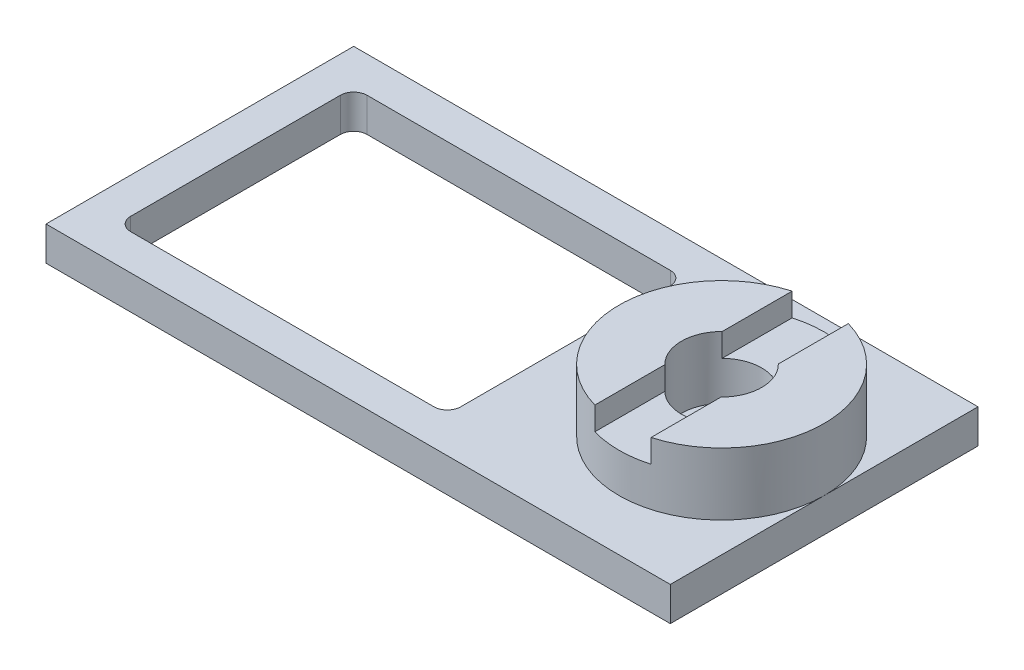
SolidWorks part; units mm, degrees
ref_plane "Alzado" through (0, 0, 0) normal (0, 0, 1) x (1, 0, 0)
ref_plane "Planta" through (0, 0, 0) normal (0, 1, 0) x (1, 0, 0)
ref_plane "Vista lateral" through (0, 0, 0) normal (1, 0, 0) x (0, 0, -1)
sketch "Croquis1" plane through (0, 0, 0) normal (0, 1, 0) x (1, 0, 0)
  line L1 (-350, -172.5) -> (350, -172.5)
  line L2 (-350, -172.5) -> (-350, 172.5)
  line L3 (-350, 172.5) -> (350, 172.5)
  line L4 (350, -172.5) -> (350, 172.5)
  line L5 (-350, -172.5) -> (350, 172.5) construction
  line L6 (-350, 172.5) -> (350, -172.5) construction
  point P0 (0, 0)
  dimension "D1" = 345
  dimension "D2" = 700
extrude "Saliente-Extruir1" add sketch "Croquis1" along normal blind 38.1
sketch "Croquis2" plane through (0, 38.1, 0) normal (0, 1, 0) x (1, 0, 0)
  line L0 (-350, 0) -> (350, 0) construction
  line L1 (-350, 172.5) -> (-350, -172.5) construction
  line L2 (350, -172.5) -> (350, 172.5) construction
  line L3 (350, 172.5) -> (-350, 172.5) construction
  line L4 (60, -132.5) -> (-310, -132.5)
  line L5 (60, -132.5) -> (60, 132.5)
  line L6 (60, 132.5) -> (-310, 132.5)
  line L7 (-310, -132.5) -> (-310, 132.5)
  line L8 (60, -132.5) -> (-310, 132.5) construction
  line L9 (60, 132.5) -> (-310, -132.5) construction
  point P6 (-125, 0)
  dimension "D1" = 40
  dimension "D2" = 40
  dimension "D3" = 370
extrude "Cortar-Extruir1" cut sketch "Croquis2" against normal blind 38.1
fillet "Redondeo1" radius 15 4 edges at (-310, 19.05, -132.5) (-310, 19.05, 132.5) (60, 19.05, 132.5) (60, 19.05, -132.5)
sketch "Croquis3" plane through (0, 38.1, 0) normal (0, 1, 0) x (1, 0, 0)
  line L0 (235, 172.5) -> (235, -172.5) construction
  line L1 (350, 172.5) -> (-350, 172.5) construction
  line L2 (-350, -172.5) -> (350, -172.5) construction
  line L3 (350, -172.5) -> (350, 172.5) construction
  circle A0 centre (235, 0) radius 115
  dimension "D2" = 230
  dimension "D1" = 115
extrude "Saliente-Extruir2" add sketch "Croquis3" along normal blind 70
sketch "Croquis4" plane through (0, 108.1, 0) normal (0, 1, 0) x (1, 0, 0)
  circle A0 centre (235, 0) radius 45
  dimension "D1" = 90
extrude "Cortar-Extruir2" cut sketch "Croquis4" against normal blind 70
sketch "Croquis5" plane through (0, 108.1, 0) normal (0, 1, 0) x (1, 0, 0)
  line L1 (203.5, -123.5371) -> (266.5, -123.5371)
  line L2 (203.5, -123.5371) -> (203.5, 123.5371)
  line L3 (203.5, 123.5371) -> (266.5, 123.5371)
  line L4 (266.5, -123.5371) -> (266.5, 123.5371)
  line L5 (203.5, -123.5371) -> (266.5, 123.5371) construction
  line L6 (203.5, 123.5371) -> (266.5, -123.5371) construction
  point P0 (235, 0)
  dimension "D1" = 63
extrude "Cortar-Extruir3" cut sketch "Croquis5" against normal blind 26
